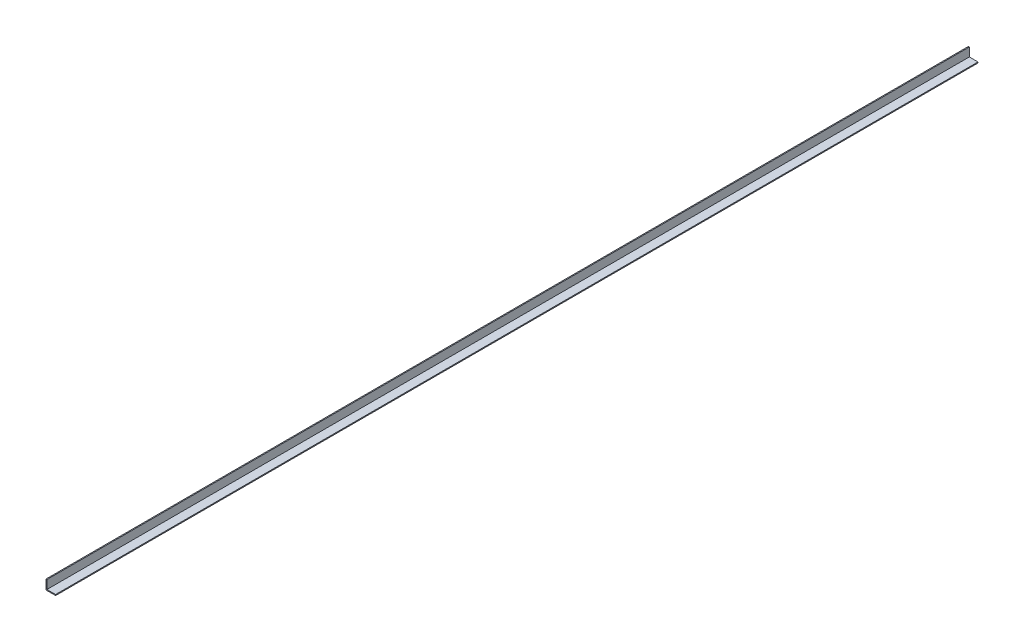
SolidWorks part; units mm, degrees
material "ASTM A36 Acero"
ref_plane "Alzado" through (0, 0, 0) normal (0, 0, 1) x (1, 0, 0)
ref_plane "Planta" through (0, 0, 0) normal (0, 1, 0) x (1, 0, 0)
ref_plane "Vista lateral" through (0, 0, 0) normal (1, 0, 0) x (0, 0, -1)
sketch "Croquis1" plane through (0, 0, 0) normal (0, 0, 1) x (1, 0, 0)
  line L0 (0, 63.5) -> (0, 0)
  line L1 (0, 0) -> (63.5, 0)
  line L2 (63.5, 0) -> (63.5, 6.35)
  line L3 (63.5, 6.35) -> (6.35, 6.35)
  line L4 (6.35, 6.35) -> (6.35, 63.5)
  line L5 (6.35, 63.5) -> (0, 63.5)
  dimension "D1" = 6.35
  dimension "D2" = 63.5
extrude "Saliente-Extruir1" add sketch "Croquis1" against normal blind 6100
